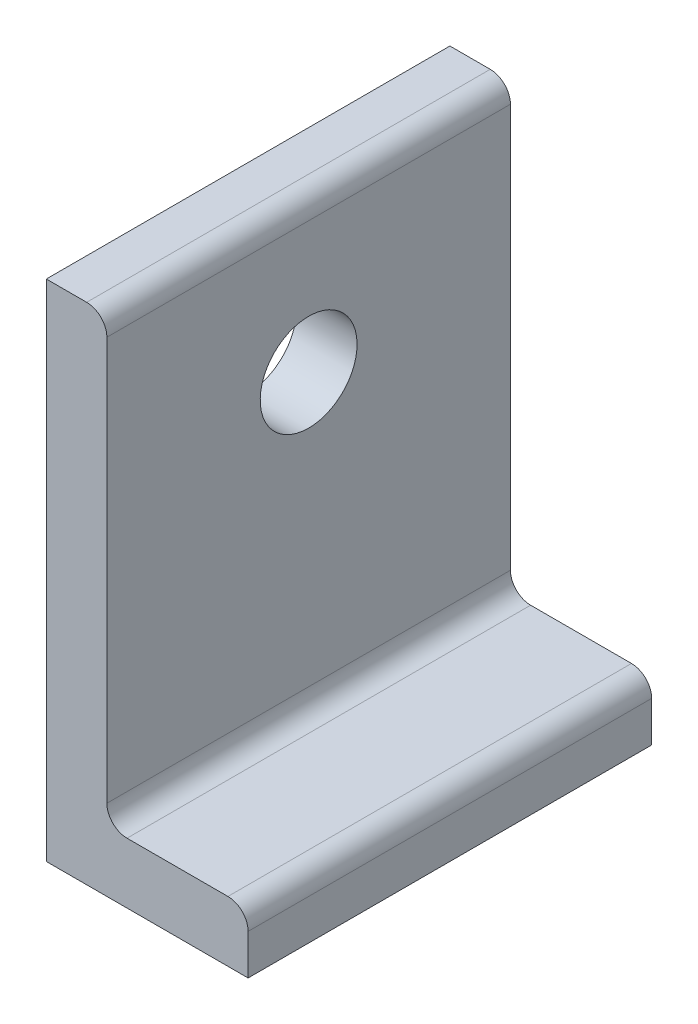
SolidWorks part; units mm, degrees
ref_plane "前视基准面" through (0, 0, 0) normal (0, 0, 1) x (1, 0, 0)
ref_plane "上视基准面" through (0, 0, 0) normal (0, 1, 0) x (1, 0, 0)
ref_plane "右视基准面" through (0, 0, 0) normal (1, 0, 0) x (0, 0, -1)
other "Configuration Table"
sketch "草图1" plane through (0, 0, 0) normal (0, 0, 1) x (1, 0, 0)
  line L0 (0, 25) -> (0, 0)
  line L1 (0, 0) -> (10, 0)
  line L2 (10, 0) -> (10, 3)
  line L3 (10, 3) -> (3, 3)
  line L4 (3, 3) -> (3, 25)
  line L5 (3, 25) -> (0, 25)
  dimension "D1" = 3
  dimension "D2" = 3
  dimension "D3" = 10
  dimension "D4" = 25
extrude "凸台-拉伸1" add sketch "草图1" along normal blind 20
sketch "草图2" plane through (0, 0, 0) normal (-1, 0, 0) x (0, 0, 1)
  line L0 (10, 25.0412) -> (10, -4.6271) construction
  line L1 (20, 25) -> (20, 0) construction
  line L2 (0, 25) -> (0, 0) construction
  line L3 (20, 0) -> (0, 0) construction
  circle A0 centre (10, 17.5) radius 2.4
  dimension "D1" = 4.8
  dimension "D2" = 17.5
extrude "切除-拉伸1" cut sketch "草图2" against normal blind 15
fillet "圆角1" radius 1 3 edges at (10, 3, 10) (3, 25, 10) (3, 3, 10)
